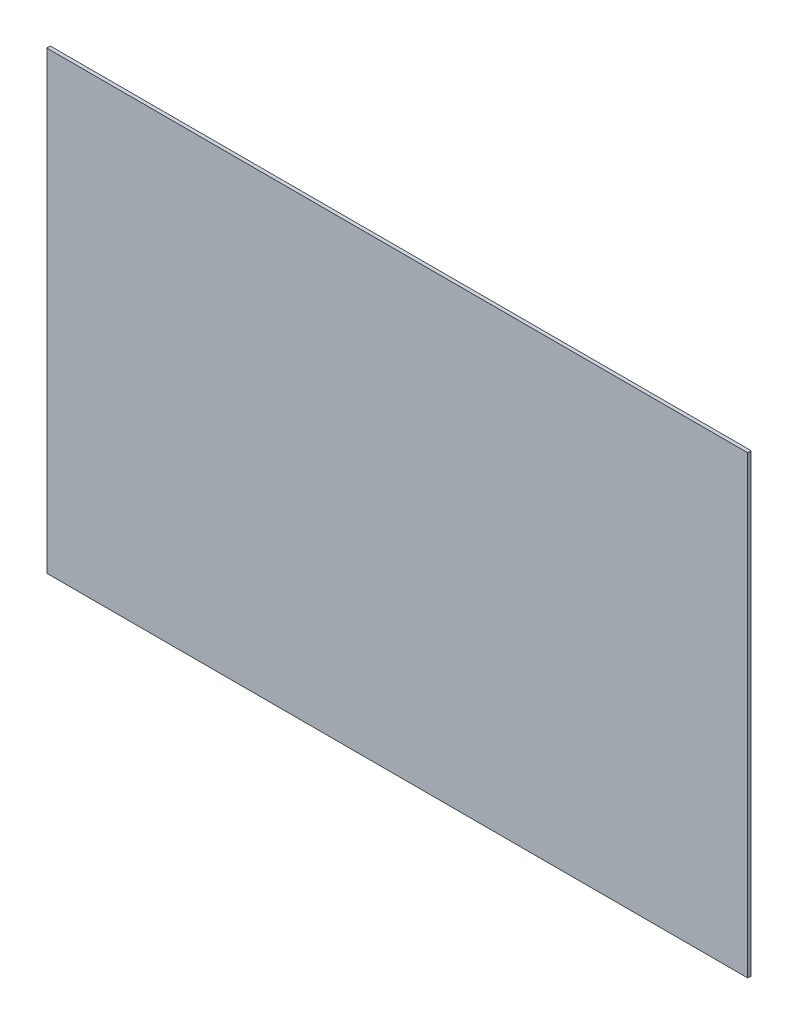
SolidWorks part; units mm, degrees
material "Custom Plastic"
ref_plane "X-Y Datum" through (0, 0, 0) normal (0, 0, 1) x (1, 0, 0)
ref_plane "X-Z Datum" through (0, 0, 0) normal (0, 1, 0) x (1, 0, 0)
ref_plane "Y-Z Datum" through (0, 0, 0) normal (1, 0, 0) x (0, 0, -1)
sketch "Sketch1" plane through (0, 0, 0) normal (0, 0, 1) x (1, 0, 0)
  line L1 (-149.85, 97.25) -> (149.85, 97.25)
  line L2 (-149.85, 97.25) -> (-149.85, -97.25)
  line L3 (-149.85, -97.25) -> (149.85, -97.25)
  line L4 (149.85, 97.25) -> (149.85, -97.25)
  line L5 (-149.85, 97.25) -> (149.85, -97.25) construction
  line L6 (-149.85, -97.25) -> (149.85, 97.25) construction
  point P0 (0, 0)
  dimension "D1" = 299.7
  dimension "D2" = 194.5
extrude "Boss-Extrude1" add sketch "Sketch1" along normal blind 1.5
sketch "Sketch2" plane through (0, 0, 1.5) normal (0, 0, 1) x (1, 0, 0)
  point P0 (80, 90.9)
  point P1 (0, 90.9)
  point P3 (-80, 90.9)
  point P5 (-123.85, 90.9)
  point P7 (-133.85, 90.9)
  point P9 (123.85, 90.9)
  point P11 (133.85, 90.9)
  point P13 (-140.6875, 17.6)
  point P15 (140.6875, -6.4)
  point P17 (-63.25, -76.35)
  point P19 (63.25, -76.35)
  point P21 (0, -76.35)
  point P23 (142.35, -89)
  point P25 (132.35, -89)
  point P27 (-132.35, -89)
  point P29 (-142.35, -89)
  point P31 (110.25, -87.9058)
  point P33 (85.25, -87.9058)
  point P35 (-85.25, -87.9058)
  point P37 (-110.25, -87.9057)
